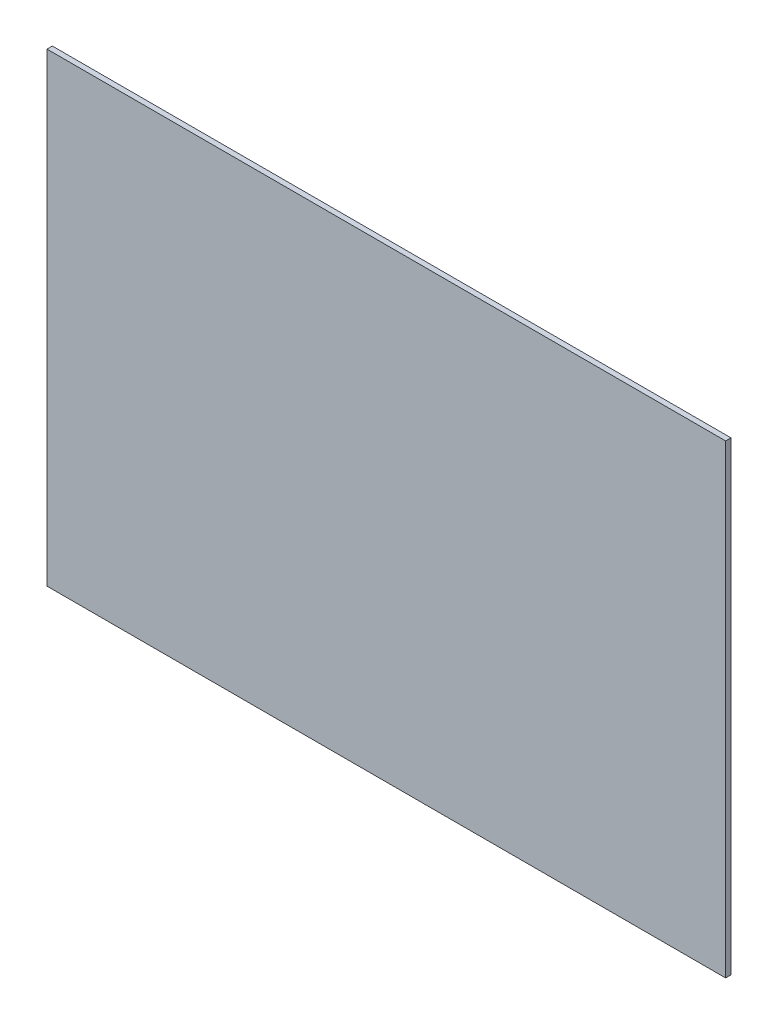
SolidWorks part; units mm, degrees
ref_plane "Front Plane" through (0, 0, 0) normal (0, 0, 1) x (1, 0, 0)
ref_plane "Top Plane" through (0, 0, 0) normal (0, 1, 0) x (1, 0, 0)
ref_plane "Right Plane" through (0, 0, 0) normal (1, 0, 0) x (0, 0, -1)
sketch "Sketch4" plane through (0, 0, 0) normal (0, 0, 1) x (1, 0, 0)
  line L0 (-124.8745, 31.4675) -> (197.9595, 31.4675)
  line L1 (-124.8745, 31.4675) -> (-124.8745, -189.7665)
  line L2 (197.9595, 31.4675) -> (197.9595, -189.7665)
  line L3 (-124.8745, -189.7665) -> (197.9595, -189.7665)
extrude "Boss-Extrude4" add sketch "Sketch4" along normal blind 2.54 contours L1 L3 L2 L0
